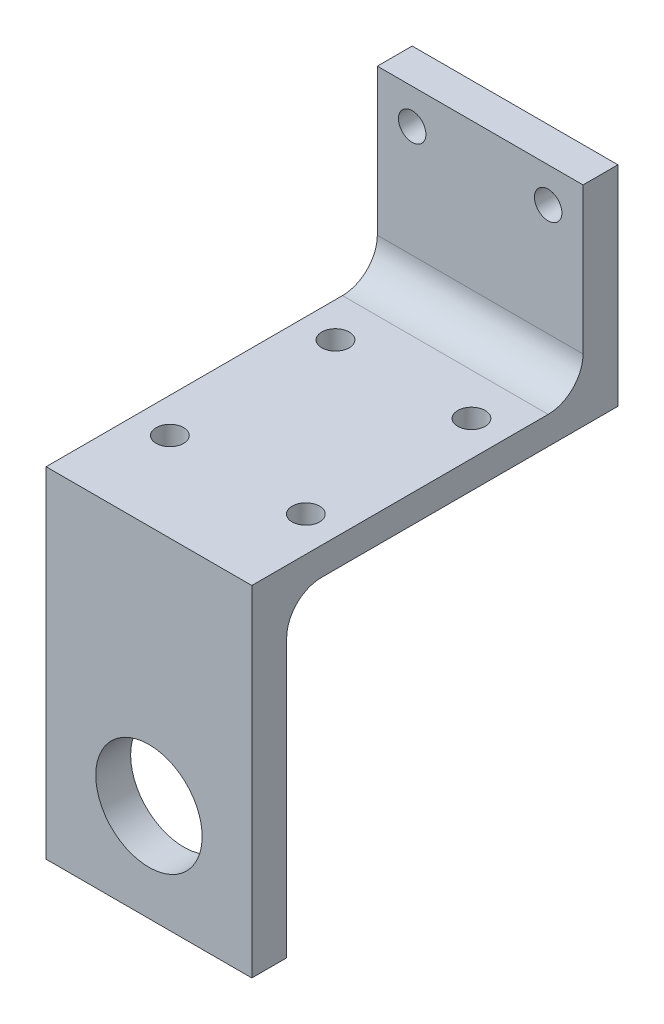
SolidWorks part; units mm, degrees
ref_plane "Front Plane" through (0, 0, 0) normal (0, 0, 1) x (1, 0, 0)
ref_plane "Top Plane" through (0, 0, 0) normal (0, 1, 0) x (1, 0, 0)
ref_plane "Right Plane" through (0, 0, 0) normal (1, 0, 0) x (0, 0, -1)
sketch "Sketch2" plane through (0, 0, 0) normal (1, 0, 0) x (0, 0, -1)
  line L3 (6.6098, -8.8508) -> (6.6098, 17.5652)
  line L4 (6.6098, 17.5652) -> (11.6898, 17.5652)
  line L5 (11.6898, 17.5652) -> (11.6898, -12.9148)
  line L6 (11.6898, -12.9148) -> (-41.6502, -12.9148)
  line L12 (6.6098, -8.8508) -> (-41.6502, -8.8508)
  line L13 (-41.6502, -8.8508) -> (-41.6502, -12.9148)
  line L15 (-41.6502, -12.9148) -> (-36.5702, -12.9148)
  line L16 (-41.6502, -12.9148) -> (-41.6502, -58.3808)
  line L17 (-41.6502, -58.3808) -> (-36.5702, -58.3808)
  line L18 (-36.5702, -12.9148) -> (-36.5702, -58.3808)
  dimension "D1" = 53.34
  dimension "D2" = 5.08
  dimension "D3" = 4.064
  dimension "D4" = 30.48
  dimension "D5" = 5.08
  dimension "D6" = 45.466
extrude "Boss-Extrude1" add sketch "Sketch2" along normal blind 29.972 contours L18 L6 L16 L17
fillet "Fillet1" radius 5.08 2 edges at (14.986, -8.8508, -6.6098) (14.986, -12.9148, 36.5702)
sketch "Sketch3" plane through (0, 0, -11.6898) normal (0, 0, -1) x (-1, 0, 0)
  line L2 (-29.972, 17.5652) -> (0, 17.5652) construction
  circle A0 centre (-24.892, 12.4852) radius 2
  circle A1 centre (-5.08, 12.4852) radius 2
  circle A2 centre (-5.08, -11.6448) radius 4
  circle A3 centre (-24.892, -11.6448) radius 4
  dimension "D1" = 5.08
  dimension "D4" = 4
  dimension "D5" = 4
  dimension "D6" = 8
  dimension "D7" = 8
  dimension "D2" = 5.08
  dimension "D3" = 5.08
  dimension "D8" = 24.13
extrude "Cut-Extrude1" cut sketch "Sketch3" against normal up to surface (5.08 mm away) up to face at (14.986, 6.8972, -6.6098)
sketch "Sketch4" plane through (0, -12.9148, 0) normal (0, -1, 0) x (1, 0, 0)
  line L3 (29.972, -11.6898) -> (29.972, 31.4902) construction
  line L4 (0, -11.6898) -> (0, 31.4902) construction
  circle A0 centre (24.892, 4.5662) radius 2
  circle A1 centre (5.08, 4.5662) radius 2
  circle A2 centre (24.892, 28.6962) radius 2
  circle A3 centre (5.08, 28.6962) radius 2
  dimension "D1" = 4
  dimension "D2" = 4
  dimension "D3" = 4
  dimension "D4" = 4
  dimension "D5" = 5.08
  dimension "D6" = 5.08
  dimension "D7" = 24.13
  dimension "D8" = 16.256
extrude "Cut-Extrude2" cut sketch "Sketch4" against normal blind 29.972
sketch "Sketch5" plane through (0, 0, 36.5702) normal (0, 0, -1) x (-1, 0, 0)
  line L0 (-29.972, -58.3808) -> (0, -58.3808) construction
  circle A0 centre (-14.986, -44.1568) radius 7.75
  point P5 (-14.986, -58.3808)
  dimension "D1" = 15.5
  dimension "D2" = 31.242
extrude "Cut-Extrude3" cut sketch "Sketch5" against normal up to surface (5.08 mm away) up to face at (14.986, -33.6158, 41.6502)
